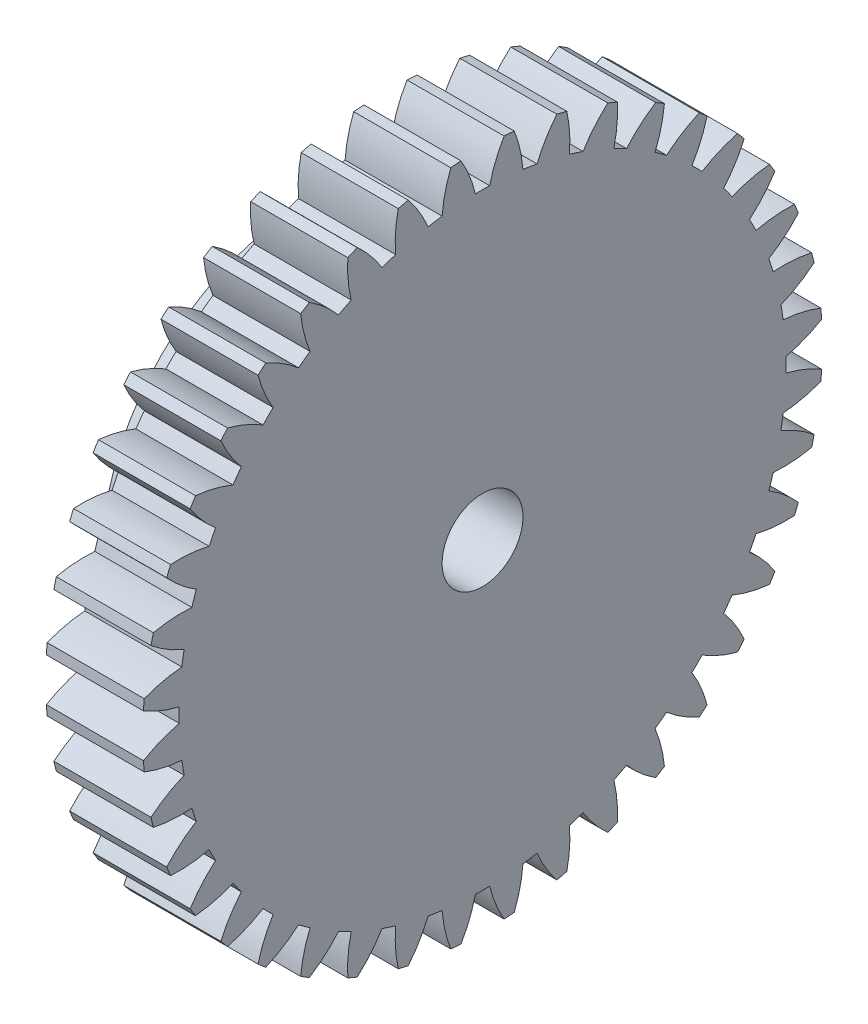
SolidWorks part; units mm, degrees
ref_plane "Plane1" through (0, 0, 0) normal (0, 0, 1) x (1, 0, 0)
ref_plane "Plane2" through (0, 0, 0) normal (0, 1, 0) x (1, 0, 0)
ref_plane "Plane3" through (0, 0, 0) normal (1, 0, 0) x (0, 0, -1)
sketch "HoldingSke" plane through (0, 0, 0) normal (0, 1, 0) x (1, 0, 0)
  line L0 (0, 0) -> (0.383, -0.3214)
  line L1 (-15, 0) -> (100, 0) construction
  line L2 (0, 0) -> (-2.1039, 2.3779)
  line L3 (0, 0) -> (-11.863, 4.5341)
  line L4 (0, 0) -> (6.6156, 5.5511)
  line L5 (0, 0) -> (-46.8476, -17.4728)
  line L6 (0, 0) -> (-9.9476, -6.7116)
  line L7 (-2.1039, 2.3779) -> (8.6586, 51.2059)
  line L8 (-76.2, 54.61) -> (-74.4, 54.61)
  line L9 (-71.009, 38.7566) -> (-53.1078, 45.2721)
  line L10 (-76.2, 71.12) -> (104.1128, 71.12)
  line L11 (0, 0) -> (-12, 0)
  line L12 (-76.2, 101.6) -> (-76.133, 101.6)
  line L13 (24.9733, 27.94) -> (52.9518, 28.4284)
  line L14 (24.9733, 27.94) -> (24.9743, 27.94)
  line L15 (24.9733, 27.94) -> (100.4006, 29.5858)
  line L16 (-63.627, -2) -> (-12.827, -2)
  circle A0 centre (0, 0) radius 5
  circle A1 centre (0, 0) radius 37.499
  circle A2 centre (0, 0) radius 37.5
  circle A3 centre (0, 0) radius 5
  dimension "MHD" = 74.998
  dimension "Hub_dia" = 75
  dimension "Bore" = 10
  dimension "MBD" = 10
  dimension "Num_teeth" = 40
  dimension "Pitch" = 0.5
  dimension "Overall_len" = 50
  dimension "Show_teeth" = 40
  dimension "Thickness" = 12
  dimension "OAL" = 50.0001
  dimension "T_dim" = 1.8
  dimension "Ap" = 20
  dimension "H" = 19.05
  dimension "Pitch_radius" = 180.3128
  dimension "Width" = 12
  dimension "Backlash" = 0.067
  dimension "Addendum_fac" = 1
  dimension "Dedendum_fac" = 1.25
  dimension "Clearance_fac" = 0.25
  dimension "Dedendum_add" = 0.001
  dimension "Module" = 2
sketch "BasProSke" plane through (0, 0, 0) normal (0, 1, 0) x (1, 0, 0)
  line L0 (-10, 0) -> (60, 0) construction
  line L1 (0, 0) -> (0, 42)
  line L2 (0, 0) -> (12, 0)
  line L3 (12, 0) -> (12, 42)
  line L4 (12, 42) -> (0, 42)
  dimension "Thickness" = 12
  dimension "Diameter" = 84
revolve "Base-Revolve" add sketch "BasProSke" angle 360 about L0
sketch "TooCutSke" plane through (0, 0, 0) normal (1, 0, 0) x (0, 0, -1)
  line L1 (0, 0) -> (0, 107) construction
  line L2 (0, 0) -> (-1.6876, 39.9644) construction
  line L3 (0, 0) -> (-6.2726, 79.7007) construction
  line L4 (-1.6876, 39.9644) -> (-3.1363, 39.8504) construction
  arc A0 (0.8828, 37.4886) -> (-0.8828, 37.4886) centre (0, 0) ccw
  arc A1 (2.6784, 41.94) -> (-2.6784, 41.94) centre (0, 0) ccw
  circle A2 centre (0, 0) radius 40 construction
  circle A3 centre (0, 0) radius 37.5877 construction
  arc A4 (-0.8828, 37.4886) -> (-2.6784, 41.94) centre (-16.451, 33.7965) ccw
  arc A5 (2.6784, 41.94) -> (0.8828, 37.4886) centre (16.451, 33.7965) ccw
  dimension "Root_dia" = 74.998
  dimension "Overcut_dia" = 84.0508
  dimension "Pitch_dia" = 80
  dimension "Base_dia" = 75.1754
  dimension "Flank_rad" = 16
  dimension "Half_ang" = 4.5
  dimension "Half_CT" = 1.4531
extrude "ToothCut" cut sketch "TooCutSke" along normal through all
fillet "Breaks" [suppressed] radius 0.04
fillet "RootFillets" [suppressed] radius 0.501
pattern_circular "TeethCuts" count 40 every 9 about axis through (-10, 0, 0) along (1, 0, 0) of "ToothCut", "RootFillets", "Breaks"
sketch "HubNeaOneSke" plane through (0, 0, 0) normal (-1, 0, 0) x (0, 0, 1)
  circle A0 centre (0, 0) radius 37.499
  dimension "Diameter" = 74.998
extrude "HubNearOne" [suppressed] add sketch "HubNeaOneSke" along normal blind 38.0001
sketch "HubNeaBotSke" plane through (0, 0, 0) normal (-1, 0, 0) x (0, 0, 1)
  circle A0 centre (0, 0) radius 37.499
  dimension "Diameter" = 74.998
extrude "HubNearBoth" [suppressed] add sketch "HubNeaBotSke" along normal blind 19
ref_plane "FarPln" through (12, 0, 0) normal (1, 0, 0) x (0, 0, -1)
sketch "HubFarSke" plane through (12, 0, 0) normal (1, 0, 0) x (0, 0, -1)
  circle A0 centre (0, 0) radius 37.499
  dimension "Diameter" = 74.998
extrude "HubFar" [suppressed] add sketch "HubFarSke" along normal blind 19
sketch "BorSke" plane through (0, 0, 0) normal (1, 0, 0) x (0, 0, -1)
  circle A0 centre (0, 0) radius 5
  dimension "Diameter" = 10
extrude "Bore" cut sketch "BorSke" along normal mid plane 100.0001
sketch "KeySke" plane through (0, 0, 0) normal (1, 0, 0) x (0, 0, -1)
  line L0 (-1.5, 0) -> (-1.5, 6.8)
  line L1 (-1.5, 6.8) -> (1.5, 6.8)
  line L2 (1.5, 6.8) -> (1.5, 0)
  line L3 (0, 0) -> (0, 34) construction
  line L4 (-1.5, 0) -> (1.5, 0)
  dimension "Offset" = 6.8
  dimension "Width" = 3
extrude "Keyway" [suppressed] cut sketch "KeySke" along normal mid plane 100.0001
pattern_circular "Keyway2" [suppressed] count 2 every 90 about axis through (-10, 0, 0) along (1, 0, 0)
sketch "Sketch1" plane through (0, 0, 0) normal (-1, 0, 0) x (0, 0, 1)
  circle A0 centre (0, 0) radius 25
  circle A2 centre (0, 0) radius 5
  circle A3 centre (20, 0) radius 3
  circle A4 centre (-20, 0) radius 3
  point P16 (0, 0)
  dimension "D1" = 2
extrude "Boss-Extrude1" add sketch "Sketch1" along normal blind 10
equation "' \"Module@HoldingSke\" = 6.35"
equation "' \"Num_teeth@HoldingSke\" = 12"
equation "' \"Ap@HoldingSke\" =  20"
equation "' \"Ap@HoldingSke\" = 20"
equation "' \"Width@HoldingSke\" = 0.5 * 25.4"
equation "' \"Hub_dia@HoldingSke\"= 1 * 25.4"
equation "' \"Hub_dia@HoldingSke\" = 1 * 25.4"
equation "' \"Overall_len@HoldingSke\" = 1.0 * 25.4"
equation "' \"Bore@HoldingSke\" = 0.75 * 25.4"
equation "' \"T_dim@HoldingSke\" = 0.1 * 25.4"
equation "' \"Width@KeySke\" = 0.25 * 25.4"
equation "' \"Show_teeth@HoldingSke\" = 13"
equation "' \"Backlash@HoldingSke\" = 0.009 * 25.4"
equation "' \"Addendum_fac@HoldingSke\" = 1.0"
equation "' \"Dedendum_fac@HoldingSke\" = 1.25"
equation "' \"Dedendum_add@HoldingSke\" = 0.00005 * 25.4"
equation "' \"Clearance_fac@HoldingSke\" = 0.25"
equation "\"Pitch@HoldingSke\" = 1 / \"Module@HoldingSke\""
equation "\"Overcut_dia@TooCutSke\" = (\"Num_teeth@HoldingSke\" + 2 * \"Addendum_fac@HoldingSke\") / \"Pitch@HoldingSke\" + 0.002 * 25.4"
equation "\"Pitch_dia@TooCutSke\" = \"Num_teeth@HoldingSke\" / \"Pitch@HoldingSke\""
equation "\"Base_dia@TooCutSke\" = \"Num_teeth@HoldingSke\" / \"Pitch@HoldingSke\" * cos((\"Ap@HoldingSke\"  * 3.14159265 / 180))"
equation "\"Root_dia@TooCutSke\" = (\"Num_teeth@HoldingSke\" + 2) / \"Pitch@HoldingSke\" - 2 * (\"Addendum_fac@HoldingSke\" + \"Dedendum_fac@HoldingSke\") / \"Pitch@HoldingSke\" - \"Dedendum_add@HoldingSke\" * 2"
equation "\"Half_ang@TooCutSke\" = 180 / \"Num_teeth@HoldingSke\""
equation "\"Half_CT@TooCutSke\" = \"Num_teeth@HoldingSke\" / \"Pitch@HoldingSke\" * sin((3.14159265 / 2 / \"Num_teeth@HoldingSke\")) / 2 - 7 * \"Backlash@HoldingSke\" / 4"
equation "\"Flank_rad@TooCutSke\" = \"Num_teeth@HoldingSke\" / \"Pitch@HoldingSke\" / 5"
equation "\"Radius@RootFillets\" = \"Clearance_fac@HoldingSke\" / \"Pitch@HoldingSke\" + \"Dedendum_add@HoldingSke\""
equation "\"Break_rad@Breaks\" = 0.02 / \"Pitch@HoldingSke\""
equation "\"Thickness@HoldingSke\" = \"Width@HoldingSke\""
equation "\"OAL@HoldingSke\" = \"Thickness@HoldingSke\""
equation "\"MHD@HoldingSke\" = (\"Num_teeth@HoldingSke\" + 2) / \"Pitch@HoldingSke\" - 2 * (\"Addendum_fac@HoldingSke\" + \"Dedendum_fac@HoldingSke\")  / \"Pitch@HoldingSke\" - \"Dedendum_add@HoldingSke\" * 2"
equation "\"MBD@HoldingSke\" = (\"Num_teeth@HoldingSke\" + 2) / \"Pitch@HoldingSke\" - 2 * (\"Addendum_fac@HoldingSke\" + \"Dedendum_fac@HoldingSke\")  / \"Pitch@HoldingSke\" - \"Dedendum_add@HoldingSke\" * 2 - 0.002 * 25.4"
equation "\"MHD@HoldingSke\" = ((sgn( \"MHD@HoldingSke\" - \"Hub_dia@HoldingSke\" )-1)*( \"MHD@HoldingSke\" - \"Hub_dia@HoldingSke\" ))/-2+ \"Hub_dia@HoldingSke\""
equation "\"MBD@HoldingSke\" = ((sgn( \"MBD@HoldingSke\" - \"Bore@HoldingSke\" )-1)*( \"MBD@HoldingSke\" - \"Bore@HoldingSke\" ))/-2+ \"Bore@HoldingSke\""
equation "\"OAL@HoldingSke\" = ((sgn( \"OAL@HoldingSke\" - \"Overall_len@HoldingSke\" )+1)*( \"OAL@HoldingSke\" - \"Overall_len@HoldingSke\" ))/2 + \"Overall_len@HoldingSke\" + 0.000002 * 25.4"
equation "\"Num_teeth@TeethCuts\" = int( \"Show_teeth@HoldingSke\" ) + 1"
equation "\"Num_teeth@TeethCuts\" = ((sgn( \"Num_teeth@TeethCuts\" - \"Num_teeth@HoldingSke\" )-1)*( \"Num_teeth@TeethCuts\" - \"Num_teeth@HoldingSke\" ))/-2+ \"Num_teeth@HoldingSke\""
equation "\"Num_teeth@TeethCuts\" = ((sgn( \"Num_teeth@TeethCuts\" - 2.0)+1)*( \"Num_teeth@TeethCuts\" - 2.0))/2 +2.0"
equation "\"Angle@TeethCuts\" = 360.0 / \"Num_teeth@HoldingSke\""
equation "\"Diameter@BasProSke\" = (\"Num_teeth@HoldingSke\" + 2 * \"Addendum_fac@HoldingSke\") / \"Pitch@HoldingSke\""
equation "\"Thickness@BasProSke\"  = \"Thickness@HoldingSke\""
equation "' \"Fillet_rad@BasProSke\" =  \"Thickness@HoldingSke\" * 0.05"
equation "' \"Fillet_rad@BasProSke\" = \"Thickness@HoldingSke\" * 0.05"
equation "\"MHD@HoldingSke\" = ((sgn( \"MHD@HoldingSke\" - \"Root_dia@TooCutSke\" )-1)*( \"MHD@HoldingSke\" - \"Root_dia@TooCutSke\" ))/-2+ \"Root_dia@TooCutSke\""
equation "\"Diameter@HubNeaOneSke\" = \"MHD@HoldingSke\""
equation "\"Length@HubNearOne\" = \"OAL@HoldingSke\" - \"Thickness@BasProSke\""
equation "\"Diameter@HubNeaBotSke\" = \"MHD@HoldingSke\""
equation "\"Length@HubNearBoth\" = ( \"OAL@HoldingSke\" - \"Thickness@BasProSke\" ) / 2.0"
equation "\"Thickness@FarPln\" = \"Thickness@BasProSke\""
equation "\"Diameter@HubFarSke\" = \"MHD@HoldingSke\""
equation "\"Length@HubFar\" = ( \"OAL@HoldingSke\" - \"Thickness@BasProSke\" ) / 2.0"
equation "\"Diameter@BorSke\" = \"MBD@HoldingSke\""
equation "\"D1@Bore\" = \"OAL@HoldingSke\" * 2.0"
equation "\"D1@Keyway\" = \"OAL@HoldingSke\" * 2.0"
equation "\"Offset@KeySke\" = \"T_dim@HoldingSke\" + \"MBD@HoldingSke\" / 2.0"
